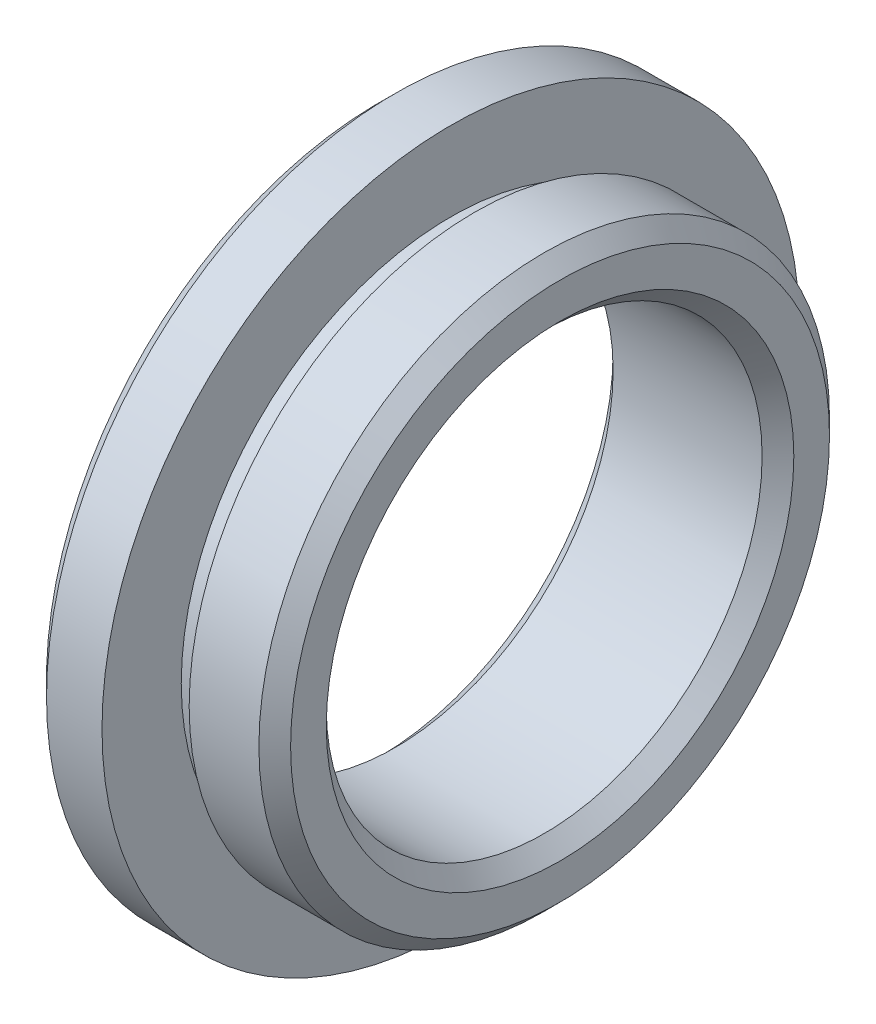
SolidWorks part; units mm, degrees
material "1.8901 (S460N)"
ref_plane "Face" through (0, 0, 0) normal (0, 0, 1) x (1, 0, 0)
ref_plane "Dessus" through (0, 0, 0) normal (0, 1, 0) x (1, 0, 0)
ref_plane "Droite" through (0, 0, 0) normal (1, 0, 0) x (0, 0, -1)
sketch "Esquisse1" plane through (0, 0, 0) normal (0, 0, 1) x (1, 0, 0)
  line L0 (0, 0) -> (61.2566, 0) construction
  line L1 (0, 13.75) -> (0, 22)
  line L2 (0, 22) -> (4.5, 22)
  line L3 (4.5, 22) -> (4.5, 17)
  line L4 (4.5, 17) -> (6, 17)
  line L5 (6, 17) -> (6, 18)
  line L6 (6, 18) -> (11.4, 18)
  line L7 (11.4, 18) -> (11.4, 13.75)
  line L8 (11.4, 13.75) -> (0, 13.75)
  dimension "D1" = 27.5
  dimension "D2" = 36
  dimension "D3" = 44
  dimension "D4" = 4.5
  dimension "D5" = 6.9
  dimension "D6" = 1.5
  dimension "D7" = 1
revolve "Révolution1" add sketch "Esquisse1" angle 360 about L0
cosmetic thread "Représentation de filetage1" parameters "D2"=34
chamfer "Chanfrein1" distance 1 angle 45 4 edges at (0, 0, 13.75) (11.4, 0, 13.75) (0, 0, 22) (11.4, 0, 18)
hole_wizard "Diamètre du perçage Ø3.1 (3.1)1" positions "Esquisse3D1" profile "Esquisse3" hole size "Ø3.1" standard "ISO"
sketch3d "Esquisse3D1"
  circle A0 centre (0, 0, 0) radius 14.75 construction
  point P0 (0, 18.5, 0)
  point P5 (14.75, 0, 0)
  dimension "D1" = 18.5
sketch "Esquisse3" plane through (0, 18.5, 0) normal (0, 1, 0) x (0, 0, 1)
  line L0 (0, 0) -> (0, 4.0313)
  line L1 (0, 4.0313) -> (1.55, 3.1)
  line L2 (1.55, 3.1) -> (1.55, 0)
  line L5 (1.55, 0) -> (0, 0)
  line L10 (0, 4.0313) -> (-1.55, 3.1) construction
  line L11 (0, -6.35) -> (0, 107.95) construction
  dimension "Diamètre du perçage" = 3.1
  dimension "Profondeur du perçage" = 3.1
  dimension "Angle de pointe" = 118
mirror "Symétrie1" about plane through (0, 0, 0) normal (0, 1, 0) of "Diamètre du perçage Ø3.1 (3.1)1"
